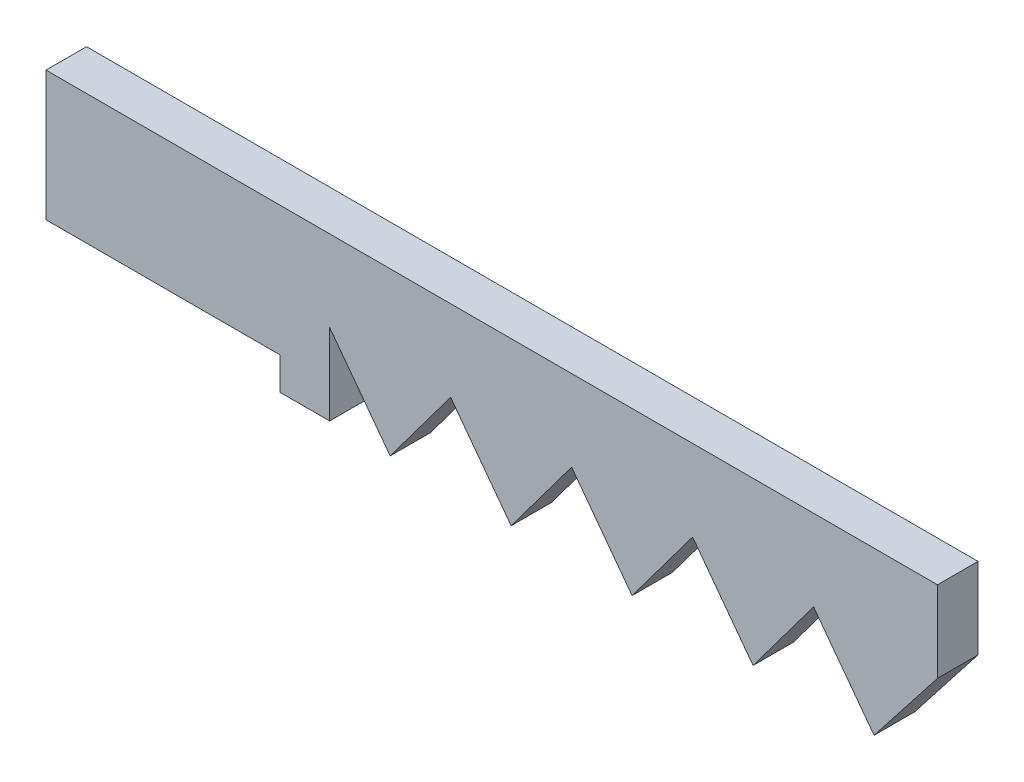
SolidWorks part; units mm, degrees
ref_plane "Front Plane" through (0, 0, 0) normal (0, 0, 1) x (1, 0, 0)
ref_plane "Top Plane" through (0, 0, 0) normal (0, 1, 0) x (1, 0, 0)
ref_plane "Right Plane" through (0, 0, 0) normal (1, 0, 0) x (0, 0, -1)
sketch "Sketch1" plane through (0, 0, 0) normal (0, 0, 1) x (1, 0, 0)
  line L0 (55, 0) -> (-55, 0) construction
  line L1 (-27.94, 0) -> (-10.16, 0)
  line L2 (-27.94, 0) -> (-27.94, 10.16)
  line L3 (-27.94, 10.16) -> (27.94, 10.16)
  line L4 (27.94, 5.08) -> (27.94, 10.16)
  line L5 (-10.16, 5.08) -> (-10.16, 0)
  line L6 (-10.16, 5.08) -> (-6.3684, 0)
  line L7 (-6.3684, 0) -> (-2.5768, 5.08)
  line L8 (-2.5768, 5.08) -> (1.2148, 0)
  line L9 (1.2148, 0) -> (5.0064, 5.08)
  line L10 (5.0064, 5.08) -> (8.798, 0)
  line L11 (8.798, 0) -> (12.5896, 5.08)
  line L12 (27.94, 5.08) -> (-10.16, 5.08) construction
  line L13 (12.5896, 5.08) -> (16.3812, 0)
  line L14 (16.3812, 0) -> (20.1728, 5.08)
  line L15 (20.1728, 5.08) -> (23.9644, 0)
  line L16 (23.9644, 0) -> (27.94, 5.08)
  point P6 (0, 10.16)
  dimension "D1" = 10.16
  dimension "D2" = 5.08
  dimension "D3" = 53.263
  dimension "D4" = 51.953
  dimension "D5" = 17.78
extrude "Boss-Extrude1" add sketch "Sketch1" along normal blind 2.54
sketch "Sketch2" plane through (0, 0, 0) normal (0, -1, 0) x (1, 0, 0)
  line L0 (55, 0) -> (-55, 0) construction
  line L1 (-27.94, 0) -> (-13.2758, 0)
  line L2 (-27.94, 0) -> (-27.94, 2.54)
  line L3 (-27.94, 2.54) -> (-13.2758, 2.54)
  line L5 (-27.94, 2.54) -> (-27.94, 0) construction
  arc A0 (-13.2758, 2.54) -> (-13.2758, 0) centre (-14.3885, 1.27) cw
  dimension "D1" = 1.6885
  dimension "D2" = 1.1127
  dimension "D3" = 14.6642
  dimension "D4" = 2.54
extrude "Cut-Extrude2" cut sketch "Sketch2" against normal blind 2.032
